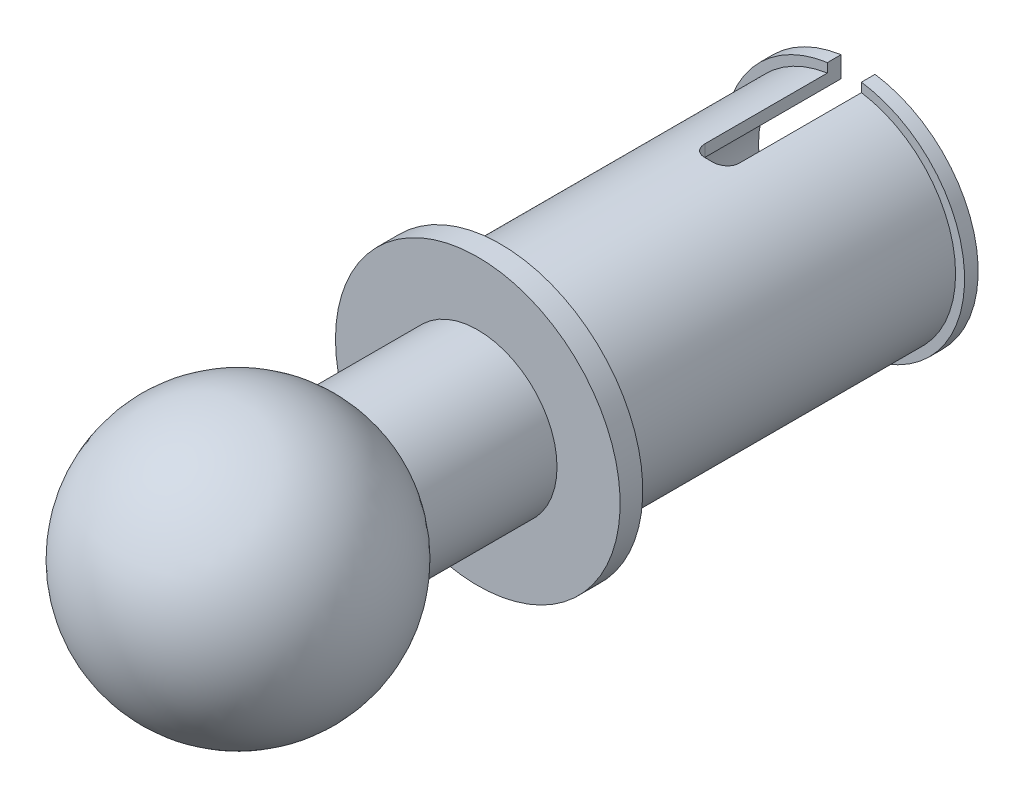
SolidWorks part; units mm, degrees
ref_plane "Front Plane" through (0, 0, 0) normal (0, 0, 1) x (1, 0, 0)
ref_plane "Top Plane" through (0, 0, 0) normal (0, 1, 0) x (1, 0, 0)
ref_plane "Right Plane" through (0, 0, 0) normal (1, 0, 0) x (0, 0, -1)
sketch "Sketch1" plane through (0, 0, 0) normal (0, 0, 1) x (1, 0, 0)
  line L0 (-2.4, 0) -> (2.4, 0)
  line L1 (-2.4, 0.895) -> (-2.4, -0.895)
  line L2 (-2.4, 0.895) -> (-0.9, 0.895)
  line L3 (0, 2.4) -> (0, -2.4)
  line L4 (-0.9, 0.895) -> (-0.9, 2.4)
  line L5 (-0.9, 2.4) -> (0.9, 2.4)
  line L6 (0.9, 0.895) -> (0.9, 2.4)
  line L7 (2.4, 0.895) -> (0.9, 0.895)
  line L8 (2.4, 0.895) -> (2.4, -0.895)
  line L9 (2.4, -0.895) -> (0.9, -0.895)
  line L10 (0.9, -0.895) -> (0.9, -2.4)
  line L11 (-0.9, -2.4) -> (0.9, -2.4)
  line L12 (-0.9, -0.895) -> (-0.9, -2.4)
  line L13 (-2.4, -0.895) -> (-0.9, -0.895)
  point P4 (0, 0)
  point P8 (-2.4, 0)
  point P12 (0, 0)
  dimension "D1" = 4.8
  dimension "D2" = 1.79
  dimension "D3" = 1.5
  dimension "D4" = 4.8
extrude "Boss-Extrude1" add sketch "Sketch1" along normal blind 7.9 contours L5 L4 L2 L1 L0 L3 | L1 L13 L12 L11 L3 L0 | L8 L7 L6 L5 L3 L0 | L3 L11 L10 L9 L8 L0
sketch "Sketch2" plane through (0, 0, 0) normal (0, 0, -1) x (-1, 0, 0)
  circle A0 centre (0, 0) radius 3.1445
extrude "Boss-Extrude3" add sketch "Sketch2" along normal blind 0.5 contours A0
sketch "Sketch3" plane through (0, 0, -0.5) normal (0, 0, -1) x (-1, 0, 0)
  circle A0 centre (0, 0) radius 2.4559
  dimension "D1" = 4.9118
extrude "Boss-Extrude4" add sketch "Sketch3" along normal blind 7.9
sketch "Sketch4" plane through (0, 0, -8.4) normal (0, 0, -1) x (-1, 0, 0)
  circle A0 centre (0, 0) radius 2.6546
extrude "Boss-Extrude5" add sketch "Sketch4" against normal blind 0.3
sketch "Sketch5" plane through (0, 0, -8.4) normal (0, 0, -1) x (-1, 0, 0)
  circle A0 centre (0, 0) radius 2.1986
extrude "Cut-Extrude1" cut sketch "Sketch5" against normal up to surface (7.9 mm away) up to face at (-2.4559, 0, -0.5)
sketch "Sketch6" plane through (0, 0, -8.4) normal (0, 0, -1) x (-1, 0, 0)
  line L0 (0, 0) -> (2.6546, 0) construction
  line L1 (0, 0) -> (0, 2.6546) construction
  line L2 (0.3755, 2.6546) -> (0.3755, 2.1663)
  line L3 (0.3755, 2.6546) -> (-0.3755, 2.6546)
  line L4 (0, 2.6546) -> (0, 2.1663)
  line L5 (0.3755, 2.1663) -> (-0.3755, 2.1663)
  line L6 (-0.3755, 2.6546) -> (-0.3755, 2.1663)
  line L7 (0.3755, -2.6546) -> (0.3755, -2.1663)
  line L8 (0.3755, -2.6546) -> (-0.3755, -2.6546)
  line L9 (-0.3755, -2.6546) -> (-0.3755, -2.1663)
  line L10 (0.3755, -2.1663) -> (-0.3755, -2.1663)
  circle A0 centre (0, 0) radius 2.6546 construction
  circle A1 centre (0, 0) radius 2.1986 construction
  circle M8 centre (0, 0) radius 2.1986
  circle M9 centre (0, 0) radius 2.6546
extrude "Cut-Extrude2" cut sketch "Sketch6" against normal blind 3.3 contours L4 L2 M9 M8 | L6 L4 M9 M8 | L9 L7 M9 M8
fillet "Fillet1" radius 0.3 4 edges at (-0.3755, -2.2967, -5.1) (0.3755, -2.2967, -5.1) (-0.3755, 2.2967, -5.1) (0.3755, 2.2967, -5.1)
sketch "Sketch7" plane through (0, 0, 0) normal (0, 0, 1) x (1, 0, 0)
  circle A0 centre (0, 0) radius 3.1445
extrude "Cut-Extrude5" cut sketch "Sketch7" along normal blind 9
sketch "Sketch8" plane through (0, 0, 0) normal (0, 0, 1) x (1, 0, 0)
  circle A0 centre (0, 0) radius 1.75
  dimension "D1" = 3.5
extrude "Boss-Extrude6" add sketch "Sketch8" along normal blind 3 contours A0
sketch "Sketch9" plane through (0, 0, 0) normal (1, 0, 0) x (0, 0, -1)
  line L0 (-5.2979, 3.0091) -> (-5.2979, -2.9909)
  arc A0 (-5.2979, -2.9909) -> (-5.2979, 3.0091) centre (-5.2979, 0.0091) ccw
  dimension "D1" = 3
revolve "Revolve1" add sketch "Sketch9" angle 360 about L0
